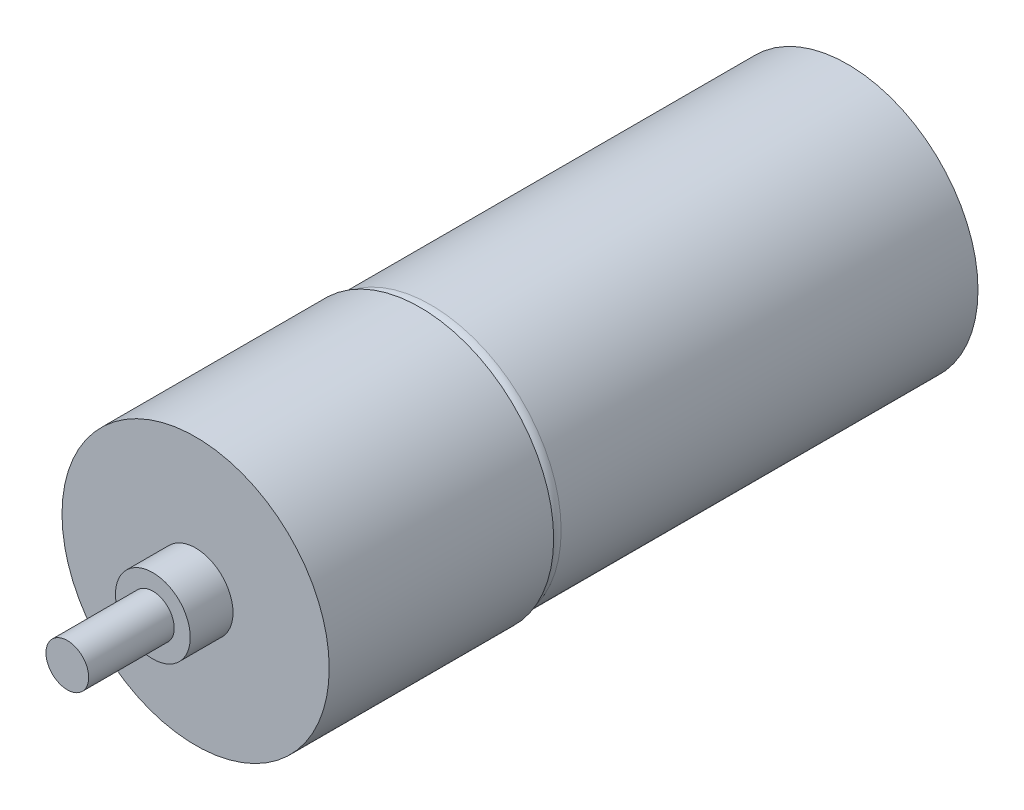
SolidWorks part; units mm, degrees
ref_plane "Front Plane" through (0, 0, 0) normal (0, 0, 1) x (1, 0, 0)
ref_plane "Top Plane" through (0, 0, 0) normal (0, 1, 0) x (1, 0, 0)
ref_plane "Right Plane" through (0, 0, 0) normal (1, 0, 0) x (0, 0, -1)
sketch "Sketch2" plane through (0, 0, 0) normal (0, 0, 1) x (1, 0, 0)
  circle A0 centre (0, 0) radius 12.2
  dimension "D1" = 24.4
extrude "Boss-Extrude1" add sketch "Sketch2" along normal blind 31
fillet "Fillet1" radius 1 1 edges at (12.2, 0, 31)
ref_plane "Plane1" through (0, 0, 31) normal (0, 0, 1) x (1, 0, 0)
sketch "Sketch3" plane through (0, 0, 31) normal (0, 0, 1) x (1, 0, 0)
  circle A0 centre (0, 0) radius 12.5
  dimension "D1" = 25
extrude "Boss-Extrude2" add sketch "Sketch3" along normal blind 21
sketch "Sketch4" plane through (0, 0, 52) normal (0, 0, 1) x (1, 0, 0)
  circle A0 centre (0, 0) radius 3.5
  dimension "D1" = 7
extrude "Boss-Extrude3" add sketch "Sketch4" along normal blind 4
sketch "Sketch5" plane through (0, 0, 56) normal (0, 0, 1) x (1, 0, 0)
  circle A0 centre (0, 0) radius 2
  dimension "D1" = 4
extrude "Boss-Extrude4" add sketch "Sketch5" along normal blind 8
sketch "Sketch6" plane through (0, 0, 0) normal (0, 0, -1) x (-1, 0, 0)
  circle A0 centre (0, 0) radius 12.2
extrude "Boss-Extrude5" add sketch "Sketch6" along normal blind 10
sketch "Sketch7" plane through (0, 0, 0) normal (1, 0, 0) x (0, 0, -1)
  line L0 (-31, 12.5) -> (-31, -12.5)
  line L1 (-31, -12.5) -> (9, -12.5)
  line L3 (9, -12.5) -> (11.2129, -12.5)
  line L4 (9, -12.5) -> (9, 18.8079)
  line L5 (9, 18.8079) -> (11.2129, 18.8079)
  line L6 (11.2129, -12.5) -> (11.2129, 18.8079)
  dimension "D1" = 40
extrude "Cut-Extrude1" cut sketch "Sketch7" against normal blind 19 and the other way blind 20 contours L3 L6 L5 L4
